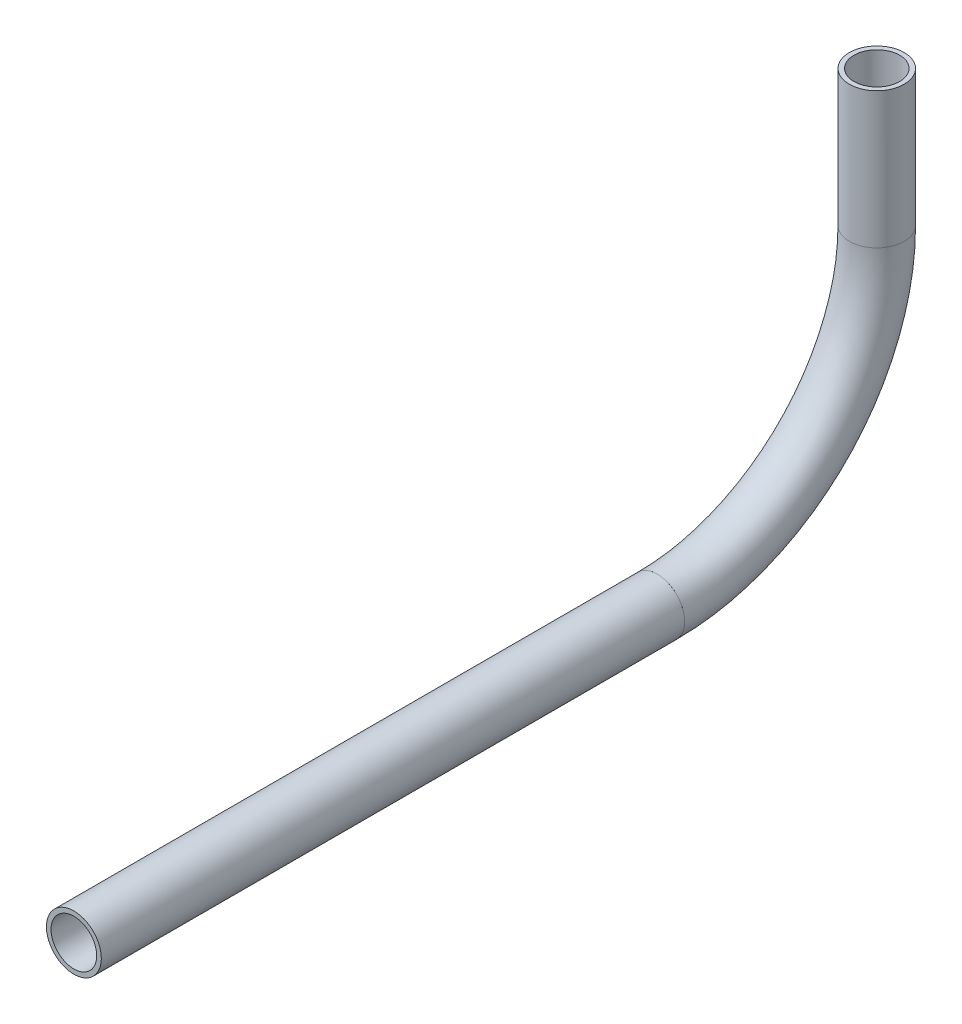
SolidWorks part; units mm, degrees
ref_plane "Front Plane" through (0, 0, 0) normal (0, 0, 1) x (1, 0, 0)
ref_plane "Top Plane" through (0, 0, 0) normal (0, 1, 0) x (1, 0, 0)
ref_plane "Right Plane" through (0, 0, 0) normal (1, 0, 0) x (0, 0, -1)
sketch "Sketch1" plane through (0, 0, 0) normal (1, 0, 0) x (0, 0, -1)
  line L0 (-303.1646, 670.1656) -> (-168.1736, 670.1656)
  line L1 (-117.3736, 720.9656) -> (-117.3736, 752.4586)
  arc A0 (-168.1736, 670.1656) -> (-117.3736, 720.9656) centre (-168.1736, 720.9656) ccw
  dimension "D1" = 50.8
other "Pipe 0.5 SCH 40(1)"
ref_plane "Plane1" through (0, 670.1656, 303.1646) normal (0, 0, -1) x (0, 1, 0)
sketch "Sketch11" plane through (0, 670.1656, 303.1646) normal (0, 0, -1) x (0, 1, 0)
  circle A0 centre (0, 0) radius 5.2832
  circle A1 centre (0, 0) radius 6.35
  point P5 (0, 0)
  dimension "In_dia" = 10.5664
  dimension "Out_dia" = 12.7
